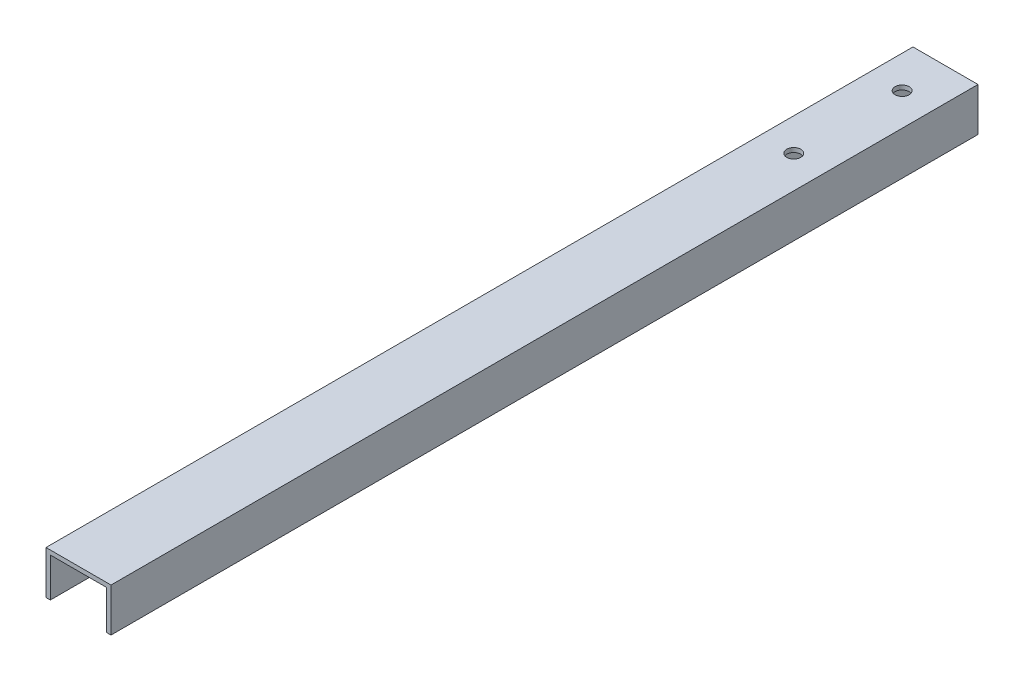
SolidWorks part; units mm, degrees
material "AISI 1020"
ref_plane "Front Plane" through (0, 0, 0) normal (0, 0, 1) x (1, 0, 0)
ref_plane "Top Plane" through (0, 0, 0) normal (0, 1, 0) x (1, 0, 0)
ref_plane "Right Plane" through (0, 0, 0) normal (1, 0, 0) x (0, 0, -1)
sketch "Sketch1" plane through (0, 0, 0) normal (0, 0, 1) x (1, 0, 0)
  line L0 (28, 0) -> (30, 0)
  line L1 (0, 0) -> (2, 0)
  line L2 (0, 0) -> (0, 20)
  line L3 (0, 20) -> (30, 20)
  line L4 (30, 0) -> (30, 20)
  line L6 (2, 0) -> (2, 18)
  line L7 (2, 18) -> (28, 18)
  line L8 (28, 0) -> (28, 18)
  dimension "D1" = 2
  dimension "D2" = 2
  dimension "D3" = 2
  dimension "D4" = 30
  dimension "D5" = 20
extrude "Boss-Extrude1" add sketch "Sketch1" along normal blind 400 contours L2 L3 L4 L0 L8 L7 L6 L1
sketch "Sketch2" plane through (0, 20, 0) normal (0, 1, 0) x (1, 0, 0)
  line L0 (15, 0) -> (15, -91.038) construction
  line L1 (0, 0) -> (30, 0) construction
  circle A0 centre (15, -70) radius 3.25
  circle A1 centre (15, -20) radius 3.25
  dimension "D1" = 6.5
  dimension "D2" = 6.5
  dimension "D3" = 20
  dimension "D4" = 50
extrude "Cut-Extrude1" cut sketch "Sketch2" against normal blind 300
